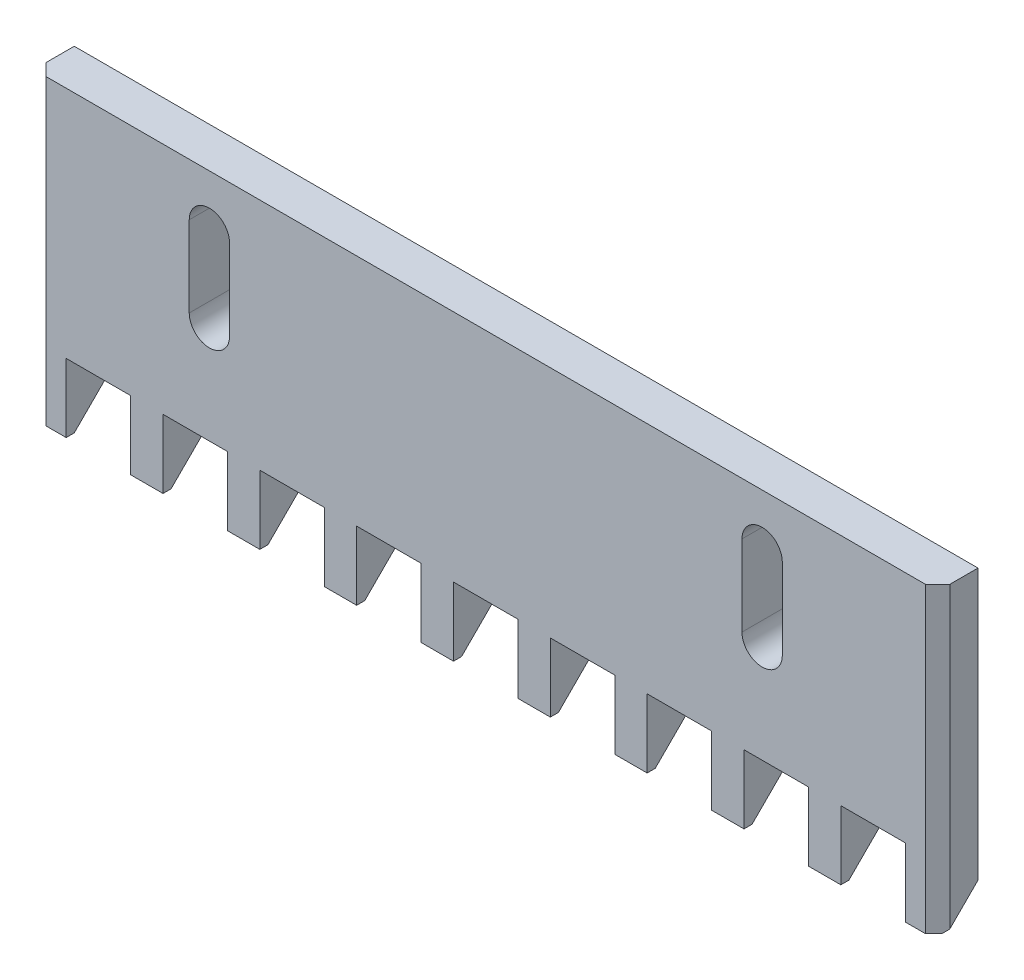
SolidWorks part; units mm, degrees
material "PE1000 Высокой плотности"
ref_plane "Спереди" through (0, 0, 0) normal (0, 0, 1) x (1, 0, 0)
ref_plane "Сверху" through (0, 0, 0) normal (0, 1, 0) x (1, 0, 0)
ref_plane "Справа" through (0, 0, 0) normal (1, 0, 0) x (0, 0, -1)
other "Configuration Table"
sketch "Эскиз1" plane through (0, 0, 0) normal (0, 0, 1) x (1, 0, 0)
  line L1 (-112, -37.5) -> (112, -37.5)
  line L2 (-112, -37.5) -> (-112, 37.5)
  line L3 (-112, 37.5) -> (112, 37.5)
  line L4 (112, -37.5) -> (112, 37.5)
  line L5 (-112, -37.5) -> (112, 37.5) construction
  line L6 (-112, 37.5) -> (112, -37.5) construction
  point P0 (0, 0)
  dimension "D1" = 224
  dimension "D2" = 75
extrude "Бобышка-Вытянуть1" add sketch "Эскиз1" along normal blind 10
sketch "Эскиз2" plane through (0, 0, 10) normal (0, 0, 1) x (1, 0, 0)
  line L6 (-68.5, 4.5) -> (-68.5, 24.5) construction
  line L7 (-73.5, 4.5) -> (-73.5, 24.5)
  line L8 (-63.5, 4.5) -> (-63.5, 24.5)
  line L13 (-112, -37.5) -> (112, -37.5) construction
  arc A4 (-73.5, 4.5) -> (-63.5, 4.5) centre (-68.5, 4.5) ccw
  arc A5 (-63.5, 24.5) -> (-73.5, 24.5) centre (-68.5, 24.5) ccw
  point P15 (-68.5, 14.5)
  dimension "D4" = 42
  dimension "D1" = 20
  dimension "D2" = 10
  dimension "D6" = 68.5
extrude "Вырез-Вытянуть1" cut sketch "Эскиз2" against normal through all both and the other way through all
mirror "Зеркальное отражение1" [suppressed] about plane through (0, 0, 0) normal (1, 0, 0)
chamfer "Фаска1" distance 8 angle 45 1 edges at (0, -37.5, 0)
sketch "Эскиз3" plane through (0, 0, 10) normal (0, 0, 1) x (1, 0, 0)
  line L1 (-8, -20.5) -> (8, -20.5)
  line L2 (-8, -20.5) -> (-8, -37.5)
  line L3 (-8, -37.5) -> (8, -37.5)
  line L4 (8, -20.5) -> (8, -37.5)
  line L90 (-112, -37.5) -> (112, -37.5) construction
  dimension "D1" = 16
  dimension "D6" = 17
  dimension "D2" = 8
extrude "Вырез-Вытянуть2" cut sketch "Эскиз3" against normal through all both and the other way through all
chamfer "Фаска2" distance 3 angle 45 2 edges at (112, 0, 10) (-112, 0, 10)
pattern_linear "Линейный массив1" count 5 spacing 24 along (-1, 0, 0) of "Вырез-Вытянуть2"
pattern_linear "Линейный массив2" count 5 spacing 24 along (1, 0, 0) of "Вырез-Вытянуть2"
sketch "Эскиз6" plane through (0, 0, 0) normal (0, 0, -1) x (-1, 0, 0)
  line L0 (-112, 37.5) -> (112, 37.5) construction
  line L1 (-12, 37.5) -> (12, 37.5)
  line L2 (-12, 37.5) -> (-12, 2.5)
  line L3 (-12, 2.5) -> (12, 2.5)
  line L4 (12, 37.5) -> (12, 2.5)
  point P6 (0, 2.5)
  dimension "D1" = 24
  dimension "D2" = 35
extrude "Вырез-Вытянуть4" [suppressed] cut sketch "Эскиз6" against normal through all both and the other way through all
pattern_linear "Линейный массив3" [suppressed] count 1 spacing 75
mirror "Зеркальное отражение2" about plane through (0, 0, 0) normal (1, 0, 0) of "Вырез-Вытянуть1"
